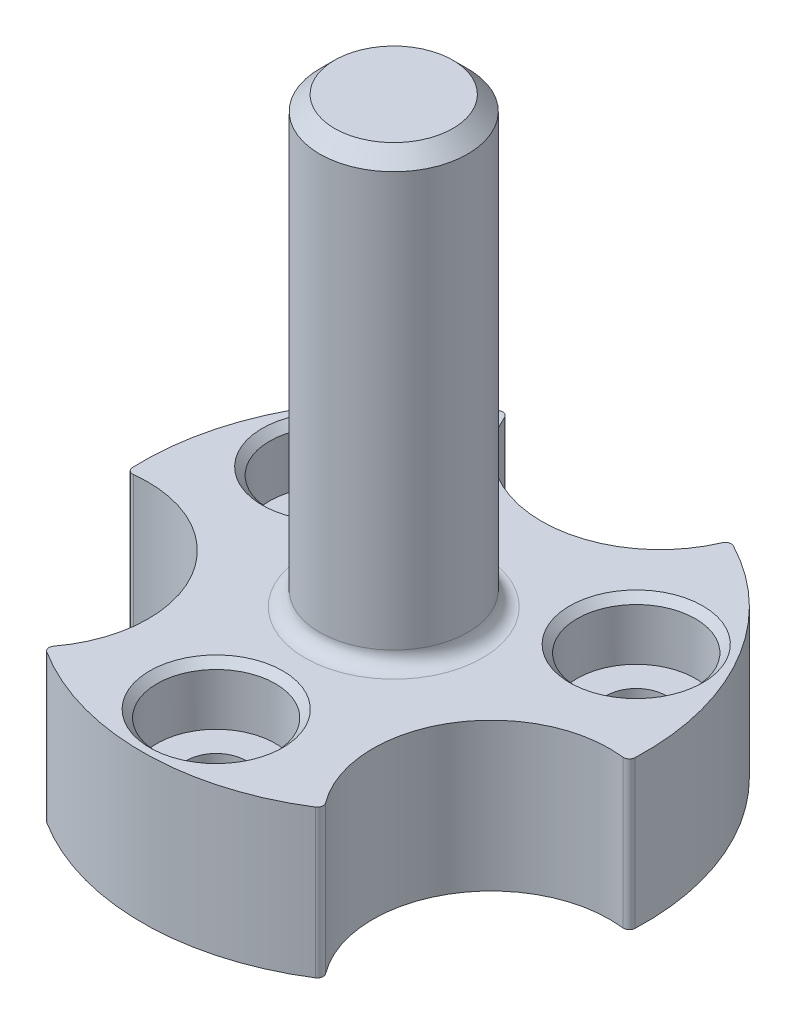
SolidWorks part; units mm, degrees
ref_plane "Front Plane" through (0, 0, 0) normal (0, 0, 1) x (1, 0, 0)
ref_plane "Top Plane" through (0, 0, 0) normal (0, 1, 0) x (1, 0, 0)
ref_plane "Right Plane" through (0, 0, 0) normal (1, 0, 0) x (0, 0, -1)
sketch "Sketch1" plane through (0, 0, 0) normal (0, 0, 1) x (1, 0, 0)
  line L0 (4.6, 0) -> (8.5, 0)
  line L1 (8.5, 0) -> (8.5, 5)
  line L2 (8.5, 5) -> (3, 5)
  line L3 (2.5, 5.5) -> (2.5, 19.5)
  line L4 (2, 20) -> (0, 20)
  line L5 (0, 20) -> (0, 2)
  line L6 (4.5, 0.1) -> (4.5, 2)
  line L7 (4.5, 2) -> (0, 2)
  line L8 (2.5, 19.5) -> (2, 20)
  line L9 (4.6, 0) -> (4.5, 0.1)
  arc A0 (2.5, 5.5) -> (3, 5) centre (3, 5.5) ccw
  point P5 (4.5, 0)
  point P6 (2.5, 20)
  dimension "D1" = 0.5
revolve "Revolve1" add sketch "Sketch1" angle 360 about L5
sketch "Sketch2" plane through (0, 0, 0) normal (0, -1, 0) x (1, 0, 0)
  line L0 (0, 10) -> (0, 0) construction
  line L1 (0, 0) -> (10, 0) construction
  line L2 (0, 0) -> (12.2474, 7.0711) construction
  circle A0 centre (7.7942, 4.5) radius 4
  circle A1 centre (0, 6) radius 1
  circle A2 centre (5.1962, -3) radius 1
  circle A3 centre (0, -9) radius 4
  circle A4 centre (-5.1962, -3) radius 1
  circle A5 centre (-7.7942, 4.5) radius 4
  point P24 (0, 0)
  dimension "D1" = 8
  dimension "D3" = 2
  dimension "D2" = 9
  dimension "D4" = 6
  dimension "D6" = 60
  dimension "D5" = 3
extrude "Cut-Extrude1" cut sketch "Sketch2" against normal up to next
fillet "Fillet1" radius 0.2 6 edges at (-3.7562, 2.5, -7.625) (3.7562, 2.5, -7.625) (-4.7253, 2.5, 7.0655) (-8.4816, 2.5, 0.5595) (8.4816, 2.5, 0.5595) (4.7253, 2.5, 7.0655)
sketch "Sketch3" plane through (0, 5, 0) normal (0, 1, 0) x (1, 0, 0)
  circle A0 centre (0, -6) radius 2
  circle A1 centre (-5.1962, 3) radius 2
  circle A2 centre (5.1962, 3) radius 2
  point P12 (0, 0)
  dimension "D1" = 4
  dimension "D2" = 3
extrude "Cut-Extrude2" cut sketch "Sketch3" against normal blind 2
chamfer "Chamfer1" distance 0.25 angle 45 3 edges at (-5.1962, 5, -1) (0, 5, 8) (5.1962, 5, -1)
